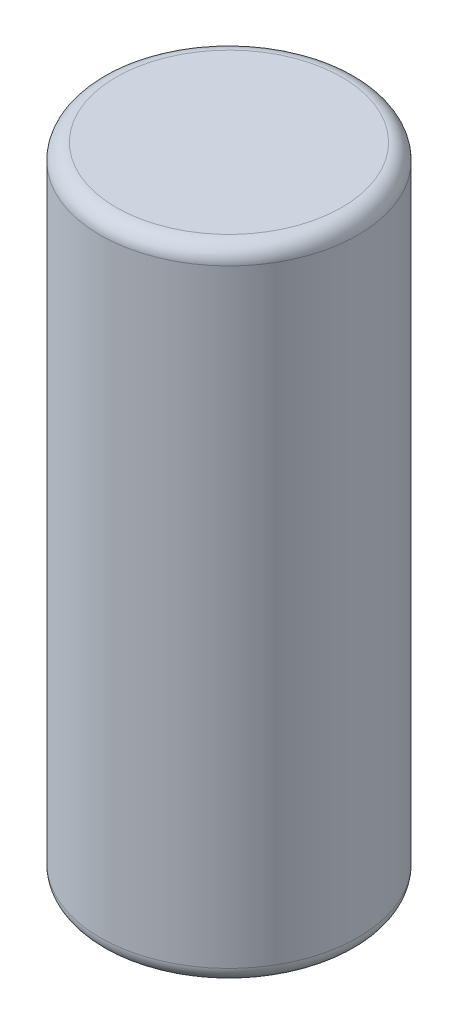
SolidWorks part; units mm, degrees
ref_plane "Front Plane" through (0, 0, 0) normal (0, 0, 1) x (1, 0, 0)
ref_plane "Top Plane" through (0, 0, 0) normal (0, 1, 0) x (1, 0, 0)
ref_plane "Right Plane" through (0, 0, 0) normal (1, 0, 0) x (0, 0, -1)
sketch "Sketch2" plane through (0, 0, 0) normal (0, 1, 0) x (1, 0, 0)
  circle A0 centre (0, 0) radius 4.025
  dimension "D1" = 8.05
extrude "Boss-Extrude1" add sketch "Sketch2" along normal blind 20
fillet "Fillet1" radius 0.5 2 edges at (0, 0, 4.025) (0, 20, 4.025)
